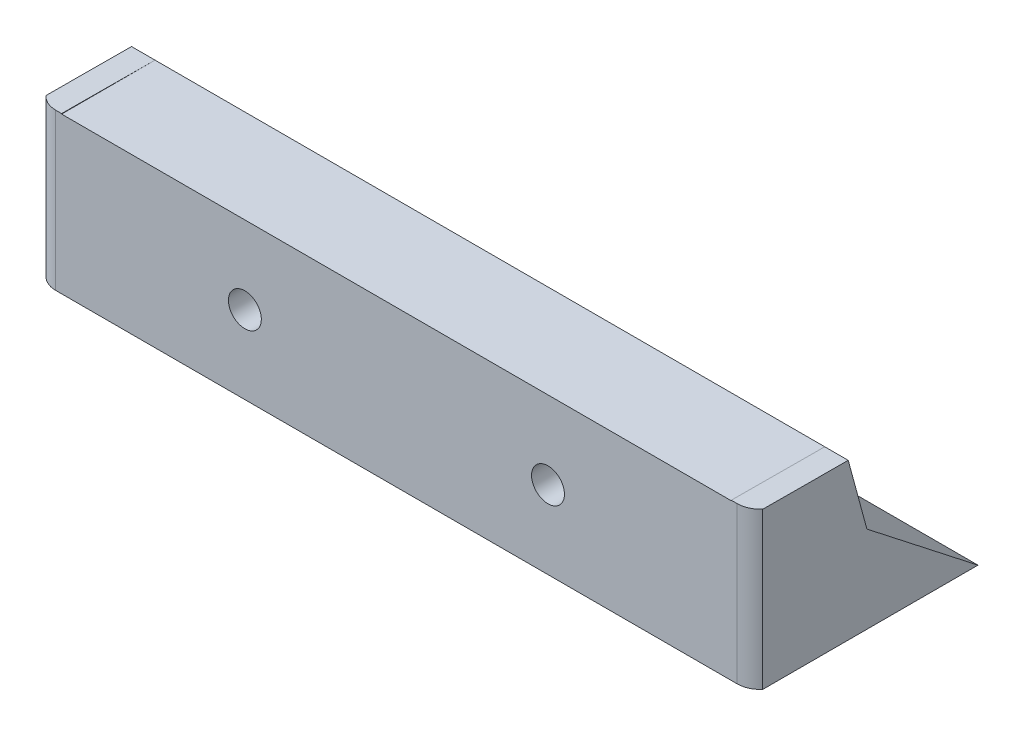
SolidWorks part; units mm, degrees
ref_plane "Front Plane" through (0, 0, 0) normal (0, 0, 1) x (1, 0, 0)
ref_plane "Top Plane" through (0, 0, 0) normal (0, 1, 0) x (1, 0, 0)
ref_plane "Right Plane" through (0, 0, 0) normal (1, 0, 0) x (0, 0, -1)
sketch "Sketch1" plane through (0, 0, 0) normal (1, 0, 0) x (0, 0, -1)
  line L0 (-4.25, 0) -> (-4.25, -4)
  line L1 (-1.45, -21) -> (17.55, -21)
  line L3 (17.55, -21) -> (8.0939, -13.6121)
  line L4 (8.0939, -13.6121) -> (4.1019, 1.1121)
  line L5 (-161.4, -23) -> (38.6, -23) construction
  line L6 (-3.6993, -5.1614) -> (-2.0007, -6.5499)
  line L7 (-1.45, -7.7112) -> (-1.45, -21)
  circle A0 centre (0, 0) radius 2.15
  arc A1 (4.1019, 1.1121) -> (-4.25, 0) centre (0, 0) ccw
  arc A2 (-4.25, -4) -> (-3.6993, -5.1614) centre (-2.75, -4) ccw
  arc A3 (-1.45, -7.7112) -> (-2.0007, -6.5499) centre (-2.95, -7.7112) ccw
  point P16 (-1.45, -7)
  dimension "D1" = 4.3
  dimension "D2" = 8.5
  dimension "D8" = 21
  dimension "D3" = 1.5
  dimension "D4" = 14
  dimension "D10" = 1.5
  dimension "D5" = 38
  dimension "D6" = 12
  dimension "D7" = 2
  dimension "D9" = 2.8
  dimension "D11" = 4
  dimension "D12" = 19
extrude "Boss-Extrude1" add sketch "Sketch1" along normal mid plane 62
sketch "Sketch2" plane through (0, 0, 4.25) normal (0, 0, 1) x (1, 0, 0)
  line L0 (31, 4.25) -> (-31, 4.25) construction
  line L1 (-28.5, 4.25) -> (28.5, 4.25)
  line L2 (-28.5, 4.25) -> (-28.5, -7.75)
  line L3 (-28.5, -7.75) -> (28.5, -7.75)
  line L4 (28.5, 4.25) -> (28.5, -7.75)
  line L5 (-31, 0) -> (-31, -4) construction
  line L6 (31, 0) -> (31, -4) construction
  dimension "D1" = 2.5
  dimension "D2" = 2.5
  dimension "D3" = 12
extrude "Cut-Extrude1" cut sketch "Sketch2" against normal up to next
sketch "Sketch7" plane through (0, 0, 4.25) normal (0, 0, 1) x (1, 0, 0)
  line L0 (0, -7.75) -> (0, -21) construction
  line L1 (-28.5, -7.75) -> (28.5, -7.75) construction
  line L2 (31, -21) -> (-31, -21) construction
  line L3 (-28.5, -8) -> (-28.5, -14.375) construction
  line L4 (-14.3, -14.375) -> (-28.5, -14.375) construction
  line L5 (-11.5, -14.375) -> (11.5, -14.375) construction
  line L6 (14.3, -14.375) -> (28.5, -14.375) construction
  line L7 (28.5, -14.375) -> (28.5, -8) construction
  line L8 (-28.5, 0) -> (-28.5, -4) construction
  line L9 (28.5, -4) -> (28.5, 0) construction
  circle A0 centre (-12.9, -14.375) radius 1.4
  circle A1 centre (12.9, -14.375) radius 1.4
  point P9 (0, -14.375)
  dimension "D1" = 2.8
  dimension "D2" = 23
extrude "Cut-Extrude2" cut sketch "Sketch7" against normal blind 9
sketch "Sketch8" plane through (31, 0, 0) normal (1, 0, 0) x (0, 0, -1)
  line L0 (-1.45, -7.7112) -> (6.5046, -7.75)
  line L1 (-3.6993, -5.1614) -> (-2.0007, -6.5499) construction
  line L2 (-4.25, 0) -> (-4.25, -4) construction
  line L3 (8.0939, -13.6121) -> (4.1019, 1.1121) construction
  line L4 (-3.6993, -5.1614) -> (-2.0007, -6.5499)
  line L5 (-4.25, 0) -> (-4.25, -4)
  line L6 (6.5046, -7.75) -> (4.1019, 1.1121)
  arc A0 (-1.45, -7.7112) -> (-2.0007, -6.5499) centre (-2.95, -7.7112) ccw construction
  arc A1 (-4.25, -4) -> (-3.6993, -5.1614) centre (-2.75, -4) ccw construction
  arc A2 (4.1019, 1.1121) -> (-4.25, 0) centre (0, 0) ccw construction
  arc A3 (-1.45, -7.7112) -> (-2.0007, -6.5499) centre (-2.95, -7.7112) ccw
  arc A4 (-4.25, -4) -> (-3.6993, -5.1614) centre (-2.75, -4) ccw
  arc A5 (4.1019, 1.1121) -> (-4.25, 0) centre (0, 0) ccw
extrude "Cut-Extrude3" cut sketch "Sketch8" against normal through all
fillet "Fillet1" radius 2 2 edges at (-31, -14.3556, 1.45) (31, -14.3556, 1.45)
sketch "Sketch9" plane through (0, -7.75, 0) normal (0, 1, 0) x (1, 0, 0)
  line L0 (31, 0.55) -> (31, 6.5046) construction
  line L1 (-30.5, -21.55) -> (30.5, -21.55)
  line L2 (-30.5, -21.55) -> (-30.5, 21.55)
  line L3 (-30.5, 21.55) -> (30.5, 21.55)
  line L4 (30.5, -21.55) -> (30.5, 21.55)
  line L5 (-30.5, -21.55) -> (30.5, 21.55) construction
  line L6 (-30.5, 21.55) -> (30.5, -21.55) construction
  line L7 (-31, -22.55) -> (31, -22.55)
  line L8 (-31, -22.55) -> (-31, 22.55)
  line L9 (-31, 22.55) -> (31, 22.55)
  line L10 (31, -22.55) -> (31, 22.55)
  line L11 (-31, -22.55) -> (31, 22.55) construction
  line L12 (-31, 22.55) -> (31, -22.55) construction
  line L13 (31, 17.55) -> (-31, 17.55) construction
  point P0 (0, 0)
  point P6 (0, 0)
  dimension "D1" = 1
  dimension "D2" = 5
  dimension "D3" = 0.5
extrude "Cut-Extrude4" cut sketch "Sketch9" against normal through all and the other way through all
